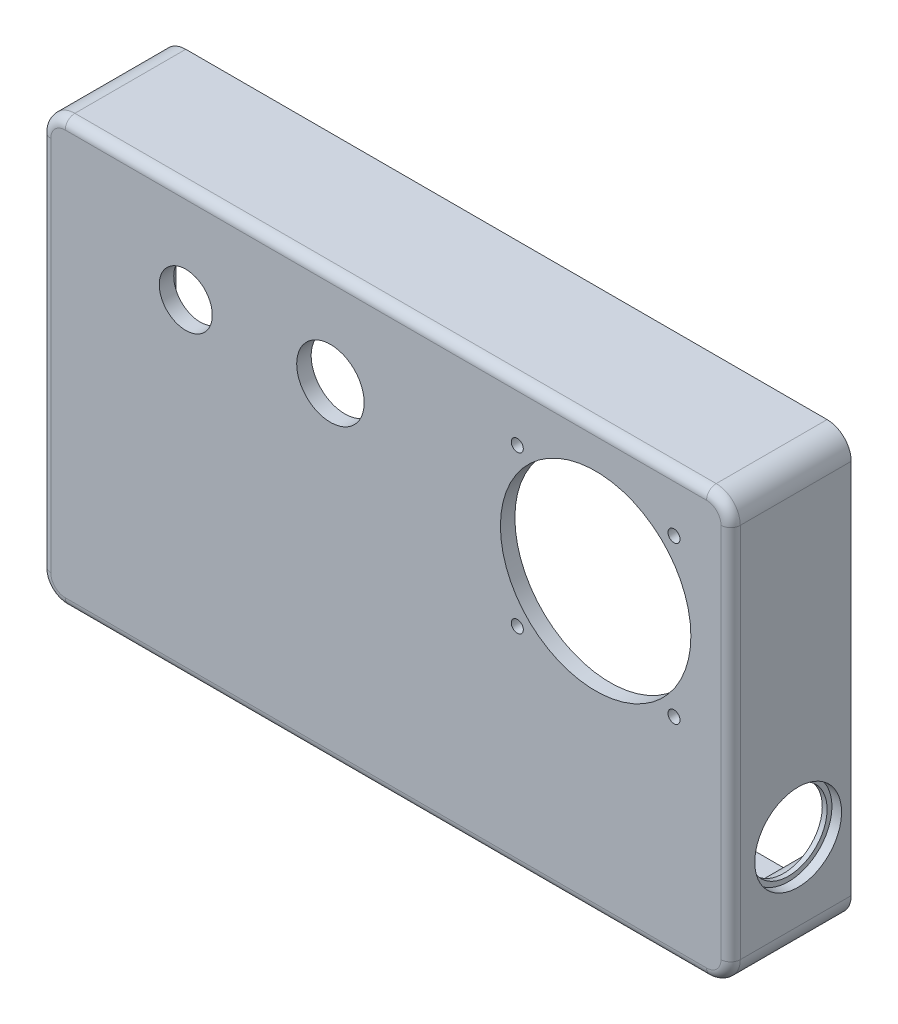
SolidWorks part; units mm, degrees
ref_plane "Front Plane" through (0, 0, 0) normal (0, 0, 1) x (1, 0, 0)
ref_plane "Top Plane" through (0, 0, 0) normal (0, 1, 0) x (1, 0, 0)
ref_plane "Right Plane" through (0, 0, 0) normal (1, 0, 0) x (0, 0, -1)
sketch "Sketch1" plane through (0, 0, 0) normal (0, 0, 1) x (1, 0, 0)
  line L0 (12.5, 41) -> (12.5, -41) construction
  line L1 (-71.5, 44) -> (71.5, 44) construction
  line L2 (-71.5, 44) -> (-71.5, -44) construction
  line L3 (-71.5, -44) -> (71.5, -44) construction
  line L4 (71.5, 44) -> (71.5, -44) construction
  line L5 (-71.5, 44) -> (71.5, -44) construction
  line L6 (-71.5, -44) -> (71.5, 44) construction
  line L7 (-48.5, 31) -> (-0.5, 31) construction
  line L8 (-48.5, 31) -> (-48.5, -28) construction
  line L9 (-48.5, -28) -> (-0.5, -28) construction
  line L10 (-0.5, 31) -> (-0.5, -28) construction
  line L11 (-48.5, 31) -> (-0.5, -28) construction
  line L12 (-48.5, -28) -> (-0.5, 31) construction
  line L13 (-68.5, 41) -> (68.5, 41) construction
  line L14 (-68.5, 41) -> (-68.5, -41) construction
  line L15 (-68.5, -41) -> (68.5, -41) construction
  line L16 (68.5, 41) -> (68.5, -41) construction
  line L17 (-68.5, 41) -> (68.5, -41) construction
  line L18 (-68.5, -41) -> (68.5, 41) construction
  line L19 (15.5, 41) -> (15.5, -41) construction
  line L20 (15.5, -14) -> (68.5, -14) construction
  line L21 (-66.5, 44) -> (66.5, 44)
  line L22 (27.25, 32.25) -> (59.75, 32.25) construction
  line L23 (27.25, 32.25) -> (27.25, -0.25) construction
  line L24 (27.25, -0.25) -> (59.75, -0.25) construction
  line L25 (59.75, 32.25) -> (59.75, -0.25) construction
  line L26 (27.25, 32.25) -> (59.75, -0.25) construction
  line L27 (27.25, -0.25) -> (59.75, 32.25) construction
  line L28 (71.5, 39) -> (71.5, -39)
  line L29 (-71.5, 39) -> (-71.5, -39)
  line L31 (-66.5, -44) -> (66.5, -44)
  circle A0 centre (43.5, 16) radius 19.75
  circle A1 centre (27.25, 32.25) radius 1.25
  circle A2 centre (59.75, 32.25) radius 1.25
  circle A3 centre (59.75, -0.25) radius 1.25
  circle A4 centre (27.25, -0.25) radius 1.25
  arc A5 (66.5, -44) -> (71.5, -39) centre (66.5, -39) ccw
  arc A6 (66.5, 44) -> (71.5, 39) centre (66.5, 39) cw
  arc A7 (-66.5, 44) -> (-71.5, 39) centre (-66.5, 39) ccw
  arc A8 (-71.5, -39) -> (-66.5, -44) centre (-66.5, -39) ccw
  point P0 (0, 0)
  point P6 (-24.5, 1.5)
  point P13 (0, 0)
  dimension "D11" = 39.5
  dimension "D16" = 2.5
  dimension "D17" = 5
  dimension "D1" = 143
  dimension "D2" = 13
  dimension "D3" = 48
  dimension "D4" = 59
  dimension "D5" = 3
  dimension "D6" = 3
  dimension "D7" = 10
  dimension "D8" = 20
  dimension "D9" = 3
  dimension "D10" = 13
  dimension "D12" = 28
  dimension "D13" = 25
  dimension "D14" = 30
  dimension "D15" = 32.5
extrude "Boss-Extrude1" add sketch "Sketch1" along normal blind 3
sketch "Sketch2" plane through (0, 0, 0) normal (0, 0, -1) x (-1, 0, 0)
  line L0 (-66.5, 44) -> (66.5, 44)
  line L1 (71.5, 39) -> (71.5, -39)
  line L2 (66.5, -44) -> (-66.5, -44)
  line L3 (-71.5, 39) -> (-71.5, -39)
  line L4 (0, 44) -> (0, -44) construction
  line L5 (-71.5, 0) -> (71.5, 0) construction
  line L6 (-61.9174, 41) -> (61.9174, 41)
  line L7 (-68.5, 34.4174) -> (-68.5, -34.4174)
  line L8 (68.5, 34.4174) -> (68.5, -34.4174)
  line L9 (-61.9174, -41) -> (61.9174, -41)
  line L10 (61.9174, -41) -> (61.9174, -37)
  line L11 (61.9174, 41) -> (61.9174, 37)
  arc A0 (-71.5, 39) -> (-66.5, 44) centre (-66.5, 39) cw
  arc A1 (66.5, 44) -> (71.5, 39) centre (66.5, 39) cw
  arc A2 (71.5, -39) -> (66.5, -44) centre (66.5, -39) cw
  arc A3 (-66.5, -44) -> (-71.5, -39) centre (-66.5, -39) cw
  circle A4 centre (-66.5, 39) radius 5 construction
  arc A5 (61.9174, 37) -> (61.9174, 41) centre (66.5, 39) ccw construction
  arc A6 (61.9174, -41) -> (61.9174, -37) centre (66.5, -39) ccw construction
  circle A7 centre (-66.5, -39) radius 5 construction
  arc A8 (-68.5, 34.4174) -> (-61.9174, 41) centre (-66.5, 39) ccw
  circle A9 centre (-66.5, 39) radius 2
  circle A10 centre (66.5, 39) radius 2
  arc A11 (68.5, 34.4174) -> (61.9174, 37) centre (66.5, 39) cw
  arc A12 (68.5, -34.4174) -> (61.9174, -37) centre (66.5, -39) ccw
  circle A13 centre (66.5, -39) radius 2
  circle A14 centre (-66.5, -39) radius 2
  arc A15 (-68.5, -34.4174) -> (-61.9174, -41) centre (-66.5, -39) cw
  point P38 (0, 41)
  point P39 (68.5, 0)
  point P44 (-68.5, 0)
  dimension "D3" = 4
  dimension "D1" = 3
  dimension "D2" = 3
extrude "Boss-Extrude2" add sketch "Sketch2" along normal blind 22
sketch "Sketch5" plane through (71.5, 0, 0) normal (1, 0, 0) x (0, 0, -1)
  line L0 (-3, -39) -> (-3, 39) construction
  line L1 (-3, -44) -> (22, -44) construction
  circle A0 centre (11, -23) radius 8
  dimension "D1" = 16
  dimension "D2" = 14
  dimension "D3" = 21
extrude "Cut-Extrude1" cut sketch "Sketch5" against normal blind 3
sketch "Sketch6" plane through (71.5, 0, 0) normal (1, 0, 0) x (0, 0, -1)
  circle A0 centre (11, -23) radius 9
  dimension "D1" = 18
extrude "Cut-Extrude2" cut sketch "Sketch6" against normal blind 2
fillet "Fillet2" radius 2 12 edges at (-70.0355, 42.5355, 3) (0, 44, 3) (70.0355, 42.5355, 3) (71.5, 0, 3) (70.0355, -42.5355, 3) (0, -44, 3) (-70.0355, -42.5355, 3) (0, -41, 0) (-68.5, 0, 0) (0, 41, 0) (68.5, 0, 0) (-71.5, 0, 3)
sketch "Sketch10" plane through (0, 0, -22) normal (0, 0, -1) x (-1, 0, 0)
  circle A0 centre (-66.5, 39) radius 2.7
  circle A1 centre (66.5, 39) radius 2.7
  circle A2 centre (66.5, -39) radius 2.7
  circle A3 centre (-66.5, -39) radius 2.7
  dimension "D1" = 5.4
extrude "Cut-Extrude4" cut sketch "Sketch10" against normal blind 4
chamfer "Chamfer1" distance 0.5 angle 45 4 edges at (63.8, -39, -22) (63.8, 39, -22) (-69.2, -39, -22) (-69.2, 39, -22)
sketch "Sketch11" plane through (0, 0, -22) normal (0, 0, -1) x (-1, 0, 0)
  line L0 (-63.75, 34.75) -> (-62.25, 34.75)
  line L1 (-23.25, -4.25) -> (-63.75, -4.25) construction
  line L2 (-23.25, -4.25) -> (-23.25, 36.25) construction
  line L3 (-23.25, 36.25) -> (-63.75, 36.25) construction
  line L4 (-63.75, -4.25) -> (-63.75, 36.25) construction
  line L5 (-23.25, -4.25) -> (-63.75, 36.25) construction
  line L6 (-23.25, 36.25) -> (-63.75, -4.25) construction
  line L7 (-62.25, 34.75) -> (-62.25, 36.25)
  arc A1 (-62.25, 36.25) -> (-63.75, 34.75) centre (-62.25, 34.75) ccw
  point P3 (-43.5, 16)
  dimension "D1" = 1.5
  dimension "D2" = 40.5
  dimension "D3" = 40.5
extrude "Cut-Extrude5" cut sketch "Sketch11" against normal up to surface (22 mm away) up to face at (28.5, -0.25, 0)
sketch "Sketch13" plane through (0, 0, -22) normal (0, 0, -1) x (-1, 0, 0)
sketch "Sketch14" plane through (0, 0, 0) normal (0, 0, -1) x (-1, 0, 0)
  line L0 (71.5, -39) -> (71.5, 39) construction
  line L1 (66.5, 44) -> (-66.5, 44) construction
  circle A0 centre (41.5, 24) radius 5.5
  circle A1 centre (11.5, 24) radius 7
  point P8 (0, 0)
  dimension "D1" = 11
  dimension "D4" = 14
  dimension "D2" = 30
  dimension "D3" = 20
  dimension "D5" = 30
extrude "Cut-Extrude6" cut sketch "Sketch14" against normal through all
